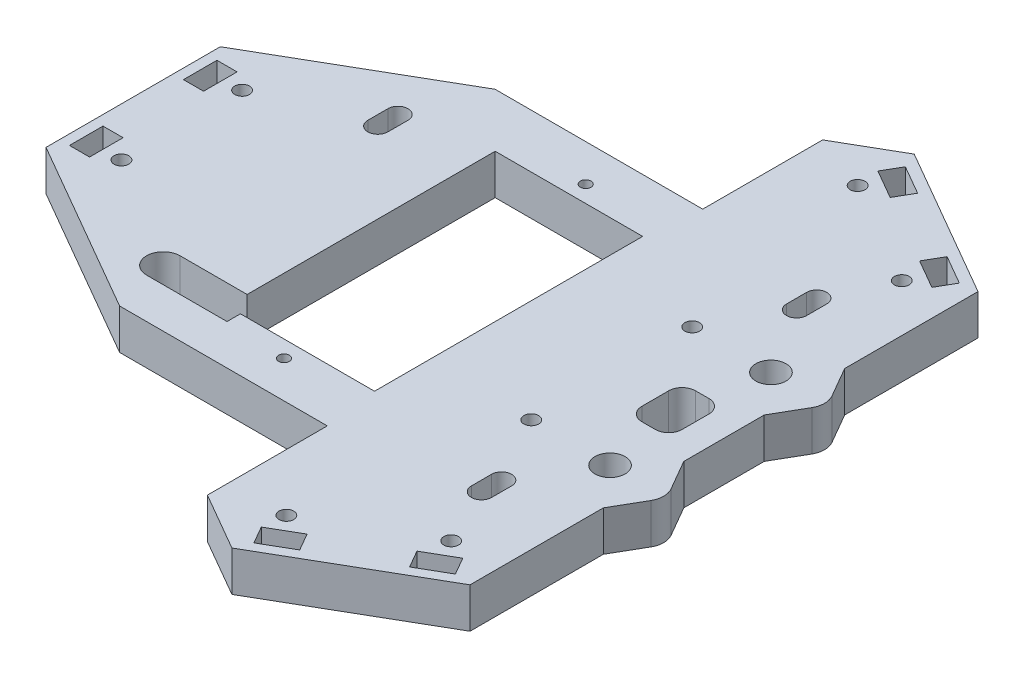
SolidWorks part; units mm, degrees
material "Acrylic (Medium-high impact)"
ref_plane "Front Plane" through (0, 0, 0) normal (0, 0, 1) x (1, 0, 0)
ref_plane "Top Plane" through (0, 0, 0) normal (0, 1, 0) x (1, 0, 0)
ref_plane "Right Plane" through (0, 0, 0) normal (1, 0, 0) x (0, 0, -1)
sketch "Sketch1" plane through (0, 0, 0) normal (0, 1, 0) x (1, 0, 0)
  line L0 (4.75, -20) -> (-15.25, -20)
  line L1 (-17.25, -17) -> (-17.25, 20)
  line L2 (-17.25, 20) -> (4.75, 20)
  line L3 (25.625, 44.3838) -> (22, 38.1051) construction
  line L4 (0, 0) -> (22, -38.1051) construction
  line L5 (0, 0) -> (-44, 0) construction
  line L6 (4.75, 20) -> (4.75, -20)
  line L7 (14.3667, 50.8838) -> (36.8833, 37.8838)
  line L8 (31.8833, 12) -> (31.8833, -12) construction
  line L9 (14.2058, 42.6051) -> (29.7942, 33.6051) construction
  line L10 (29.7942, -33.6051) -> (14.2058, -42.6051) construction
  line L11 (-44, 9) -> (-44, -9) construction
  line L12 (22, 38.1051) -> (0, 0) construction
  line L13 (22, -38.1051) -> (25.625, -44.3838) construction
  line L14 (-44, 0) -> (-51.25, 0) construction
  line L15 (0, 0) -> (31.8833, 0) construction
  line L16 (36.8833, 37.8838) -> (36.8833, -37.8838)
  line L17 (36.8833, -37.8838) -> (14.3667, -50.8838)
  line L18 (30.0712, 40.0848) -> (34.4013, 37.5848)
  line L19 (34.4013, 37.5848) -> (32.9013, 34.9867)
  line L20 (32.9013, 34.9867) -> (28.5712, 37.4867)
  line L21 (28.5712, 37.4867) -> (30.0712, 40.0848)
  line L22 (-51.25, 13) -> (-51.25, -13)
  line L23 (14.3667, 50.8838) -> (5.7064, 45.8838)
  line L24 (14.3667, -50.8838) -> (5.7064, -45.8838)
  line L25 (5.7064, 45.8838) -> (5.7064, 28)
  line L26 (5.7064, 28) -> (-25.2692, 28)
  line L27 (-25.2692, 28) -> (-51.25, 13)
  line L28 (5.7064, -45.8838) -> (5.7064, -28)
  line L29 (5.7064, -28) -> (-25.2692, -28)
  line L30 (-25.2692, -28) -> (-51.25, -13)
  line L31 (15.3487, 48.5848) -> (13.8487, 45.9867)
  line L32 (13.8487, 45.9867) -> (18.1788, 43.4867)
  line L33 (19.6788, 46.0848) -> (15.3487, 48.5848)
  line L34 (18.1788, 43.4867) -> (19.6788, 46.0848)
  line L35 (18.9288, 44.7857) -> (29.3212, 38.7857) construction
  line L36 (34.4013, -37.5848) -> (32.9013, -34.9867)
  line L37 (30.0712, -40.0848) -> (34.4013, -37.5848)
  line L38 (28.5712, -37.4867) -> (30.0712, -40.0848)
  line L39 (32.9013, -34.9867) -> (28.5712, -37.4867)
  line L40 (18.1788, -43.4867) -> (19.6788, -46.0848)
  line L41 (19.6788, -46.0848) -> (15.3487, -48.5848)
  line L42 (13.8487, -45.9867) -> (18.1788, -43.4867)
  line L43 (15.3487, -48.5848) -> (13.8487, -45.9867)
  line L44 (-49.75, -11) -> (-46.75, -11)
  line L45 (-49.75, -6) -> (-49.75, -11)
  line L46 (-46.75, -6) -> (-49.75, -6)
  line L47 (-46.75, -11) -> (-46.75, -6)
  line L48 (-46.75, 6) -> (-49.75, 6)
  line L49 (-49.75, 6) -> (-49.75, 11)
  line L50 (-46.75, 11) -> (-46.75, 6)
  line L51 (-49.75, 11) -> (-46.75, 11)
  line L52 (0, 0) -> (28.5712, 37.4867) construction
  line L53 (-15.25, -20) -> (-15.25, -22)
  line L54 (-15.25, -22) -> (-27.25, -22)
  line L56 (-27.25, -17) -> (-17.25, -17)
  line L57 (-29.25, 14.5) -> (-29.25, 17.5) construction
  line L58 (-30.75, 14.5) -> (-30.75, 17.5)
  line L59 (-27.75, 14.5) -> (-27.75, 17.5)
  line L63 (25.7064, -25) -> (25.7064, -22) construction
  line L64 (24.2064, -25) -> (24.2064, -22)
  line L65 (27.2064, -25) -> (27.2064, -22)
  line L66 (25.7064, 22) -> (25.7064, 25) construction
  line L67 (24.2064, 22) -> (24.2064, 25)
  line L68 (27.2064, 22) -> (27.2064, 25)
  line L69 (25.7064, -23.5) -> (25.7064, 0) construction
  line L70 (25.7064, 0) -> (25.7064, 23.5) construction
  line L71 (26.6333, -4) -> (32.6333, -4)
  line L72 (26.6333, -4) -> (26.6333, 4)
  line L73 (26.6333, 4) -> (32.6333, 4)
  line L74 (32.6333, -4) -> (32.6333, 4)
  line L75 (26.6333, -4) -> (32.6333, 4) construction
  line L76 (26.6333, 4) -> (32.6333, -4) construction
  circle A0 centre (14.2058, 42.6051) radius 1.1
  circle A1 centre (29.7942, 33.6051) radius 1.1
  circle A2 centre (29.7942, -33.6051) radius 1.1
  circle A3 centre (14.2058, -42.6051) radius 1.1
  circle A4 centre (-44, 9) radius 1.1
  circle A5 centre (-44, -9) radius 1.1
  circle A7 centre (14.2058, 42.6051) radius 2.5 construction
  arc A10 (24.2064, 22) -> (27.2064, 22) centre (25.7064, 22) ccw
  arc A11 (27.2064, 25) -> (24.2064, 25) centre (25.7064, 25) ccw
  arc A12 (-30.75, 14.5) -> (-27.75, 14.5) centre (-29.25, 14.5) ccw
  arc A13 (-27.75, 17.5) -> (-30.75, 17.5) centre (-29.25, 17.5) ccw
  circle A14 centre (-29.25, 14.5) radius 1.5 construction
  circle A15 centre (-29.25, 17.5) radius 1.5 construction
  arc A17 (24.2064, -25) -> (27.2064, -25) centre (25.7064, -25) ccw
  arc A18 (27.2064, -22) -> (24.2064, -22) centre (25.7064, -22) ccw
  arc A19 (-27.25, -17) -> (-27.25, -22) centre (-27.25, -19.5) ccw
  point P4 (-18.25, 0)
  point P38 (25.7064, 23.5)
  point P82 (-29.25, 16)
  point P85 (0, 0)
  point P92 (4.75, 0)
  point P93 (0, 0)
  point P102 (25.7064, -23.5)
  point P114 (29.6333, 0)
  point P148 (0, 0)
  dimension "D2" = 2.2
  dimension "D9" = 26
  dimension "D11" = 44
  dimension "D12" = 5
  dimension "D13" = 34
  dimension "D10" = 56
  dimension "D19" = 5
  dimension "D14" = 1.5
  dimension "D25" = 16
  dimension "D1" = 18
  dimension "D3" = 7.25
  dimension "D4" = 120
  dimension "D5" = 40
  dimension "D6" = 22
  dimension "D15" = 10
  dimension "D16" = 5
  dimension "D17" = 3
  dimension "D18" = 12
  dimension "D20" = 1.5
  dimension "D22" = 51.25
  dimension "D26" = 22
  dimension "D27" = 2
  dimension "D28" = 3
  dimension "D29" = 5
  dimension "D30" = 12
  dimension "D31" = 4.5
  dimension "D32" = 20
  dimension "D33" = 8
  dimension "D34" = 6
  dimension "D35" = 7.25
  dimension "D21" = 3
extrude "Boss-Extrude1" add sketch "Sketch1" along normal blind 6
sketch "Sketch10" plane through (0, 0, 0) normal (0, -1, 0) x (1, 0, 0)
  line L0 (-6.25, 22.5) -> (-6.25, -22.5) construction
  line L1 (4.75, 20) -> (4.75, -20) construction
  line L2 (4.75, -20) -> (-17.25, -20) construction
  point P4 (4.75, 0)
  point P5 (-6.25, 0)
  point P8 (-6.25, -20)
  dimension "D1" = 45
hole_wizard "Ø1.6 (1.6) Diameter Hole3" positions "3DSketch1" profile "Sketch11" hole size "Ø1.6" standard "ISO" end condition through all
sketch3d "3DSketch1"
  point P0 (-6.25, 0, 22.5)
  point P3 (-6.25, 0, -22.5)
sketch "Sketch11" plane through (-6.25, 0, 22.5) normal (1, 0, 0) x (0, 0, -1)
  line L0 (0, 0) -> (0, 6)
  line L1 (0, 6) -> (0.8, 6)
  line L2 (0.8, 6) -> (0.8, 0)
  line L5 (0.8, 0) -> (0, 0)
  line L11 (0, -6.35) -> (0, 107.95) construction
  dimension "Thru Hole Dia." = 1.6
  dimension "Thru Hole Depth" = 6
sketch "Sketch9" plane through (0, 0, 0) normal (0, -1, 0) x (1, 0, 0)
  line L0 (33.0083, -12) -> (30.7583, -12) construction
  line L1 (36.8833, 37.8838) -> (36.8833, -37.8838) construction
  line L2 (39.4814, 13.5) -> (36.8833, 18)
  line L3 (39.4814, 10.5) -> (36.8833, 6)
  line L4 (33.0083, 12) -> (30.7583, 12) construction
  line L5 (36.8833, 0) -> (0, 0) construction
  line L6 (36.8833, -18) -> (36.8833, -6)
  line L7 (39.4814, -10.5) -> (36.8833, -6)
  line L8 (39.4814, -13.5) -> (36.8833, -18)
  line L12 (36.8833, 18) -> (36.8833, 6)
  arc A0 (36.8833, 9) -> (36.8833, 15) centre (36.8833, 12) ccw
  arc A3 (36.8833, -9) -> (36.8833, -15) centre (36.8833, -12) cw
  dimension "D1" = 6
  dimension "D2" = 6
  dimension "D3" = 6
extrude "Boss-Extrude2" add sketch "Sketch9" against normal up to surface (6 mm away) contours A3 L6 | L6 A3 L7 | L8 A3 L6 | L12 A0 | A0 L12 L3 | A0 L2 L12 up to face at (-6.25, 6, 21.7)
fillet "Fillet1" radius 2 4 edges at (26.6333, 3, -4) (26.6333, 3, 4) (32.6333, 3, 4) (32.6333, 3, -4)
sketch "Sketch13" plane through (0, 6, 0) normal (0, 1, 0) x (1, 0, 0)
  line L0 (20.1333, 12) -> (20.1333, -12) construction
  line L1 (20.1333, 0) -> (34.6333, 0) construction
  line L2 (26.6333, 2) -> (26.6333, -2) construction
  line L3 (36.8833, -6) -> (36.8833, 6) construction
  line L4 (39.8833, 12) -> (31.8833, 12) construction
  line L5 (39.8833, -12) -> (31.8833, -12) construction
  arc A1 (39.4814, 10.5) -> (39.4814, 13.5) centre (36.8833, 12) ccw construction
  point P7 (26.6333, 0)
  dimension "D1" = 24
  dimension "D2" = 2.25
  dimension "D3" = 14.5
  dimension "D4" = 8
hole_wizard "Ø2.2 (2.2) Diameter Hole1" positions "3DSketch2" profile "Sketch14" hole size "Ø2.2" standard "ISO" end condition through all
sketch3d "3DSketch2"
  point P0 (20.1333, 6, -12)
  point P6 (20.1333, 6, 12)
sketch "Sketch14" plane through (20.1333, 6, -12) normal (1, 0, 0) x (0, 0, 1)
  line L0 (0, 0) -> (0, 6)
  line L1 (0, 6) -> (1.1, 6)
  line L2 (1.1, 6) -> (1.1, 0)
  line L5 (1.1, 0) -> (0, 0)
  line L11 (0, -6.35) -> (0, 107.95) construction
  dimension "Thru Hole Dia." = 2.2
  dimension "Thru Hole Depth" = 6
hole_wizard "Ø4.0mm Dowel Hole1" positions "3DSketch3" profile "Sketch15" hole size "Ø4.0" standard "ANSI Metric" end condition through all
sketch3d "3DSketch3"
  point P0 (31.8833, 6, -12)
  point P3 (31.8833, 6, 12)
sketch "Sketch15" plane through (31.8833, 6, -12) normal (1, 0, 0) x (0, 0, 1)
  line L0 (0, 0) -> (0, 6)
  line L1 (0, 6) -> (2.25, 6)
  line L2 (2.25, 6) -> (2.25, 0)
  line L5 (2.25, 0) -> (0, 0)
  line L11 (0, -6.35) -> (0, 107.95) construction
  dimension "Thru Hole Dia." = 4.5
  dimension "Thru Hole Depth" = 6
sketch "Dimensions" plane through (0, 6, 0) normal (0, 1, 0) x (1, 0, 0)
  line L0 (8.344, 0) -> (-110.844, 0)
  line L1 (20.1333, 0) -> (34.6333, 0) construction
  line L2 (53.736, 93.0735) -> (-2.486, -4.3059)
  line L4 (-1.5108, 2.6167) -> (52.7608, -91.3843)
  line L8 (36.8833, 6) -> (36.8833, -6)
  line L10 (14.3667, 50.8838) -> (36.8833, 37.8838)
  line L11 (-51.25, 13) -> (-51.25, -13)
  line L12 (14.3667, -50.8838) -> (36.8833, -37.8838)
  point P3 (-51.25, 0)
  point P7 (25.625, 44.3838)
  point P10 (25.625, -44.3838)
  dimension "D1" = 51.25
  dimension "D2" = 25.625
  dimension "D3" = 36.8833
  dimension "D4" = 51.25
  dimension "D5" = 51.25
  dimension "D6" = 51.25
  dimension "D7" = 88.7676
  dimension "D8" = 60
